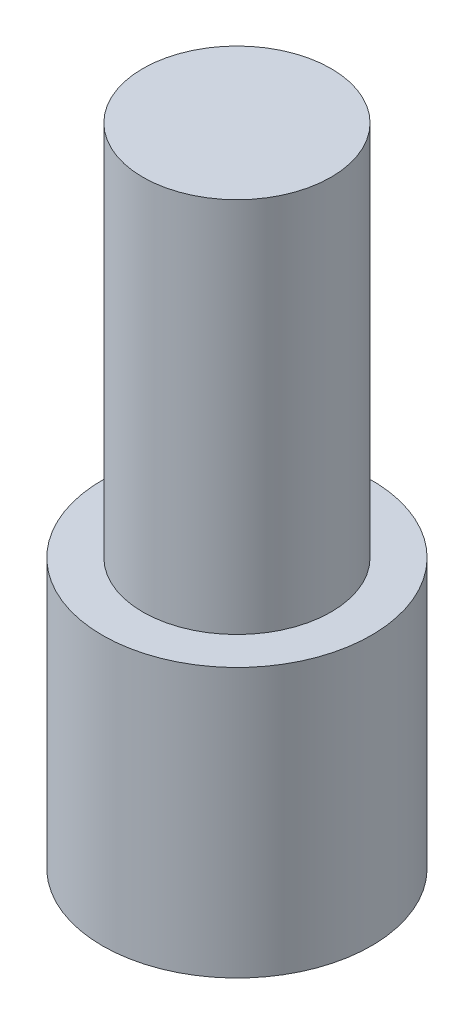
SolidWorks part; units mm, degrees
ref_plane "Front Plane" through (0, 0, 0) normal (0, 0, 1) x (1, 0, 0)
ref_plane "Top Plane" through (0, 0, 0) normal (0, 1, 0) x (1, 0, 0)
ref_plane "Right Plane" through (0, 0, 0) normal (1, 0, 0) x (0, 0, -1)
sketch "Sketch1" plane through (0, 0, 0) normal (0, 1, 0) x (1, 0, 0)
  circle A0 centre (0, 0) radius 2.5
  dimension "D1" = 5
extrude "Boss-Extrude1" add sketch "Sketch1" along normal blind 5
sketch "Sketch2" plane through (0, 5, 0) normal (0, 1, 0) x (1, 0, 0)
  circle A0 centre (0, 0) radius 1.75
  dimension "D1" = 3.5
extrude "Boss-Extrude2" add sketch "Sketch2" along normal blind 7
sketch "Sketch3" plane through (0, 0, 0) normal (0, -1, 0) x (1, 0, 0)
  circle A0 centre (0, 0) radius 1.75
  dimension "D1" = 3.5
extrude "Cut-Extrude1" cut sketch "Sketch3" against normal blind 3
